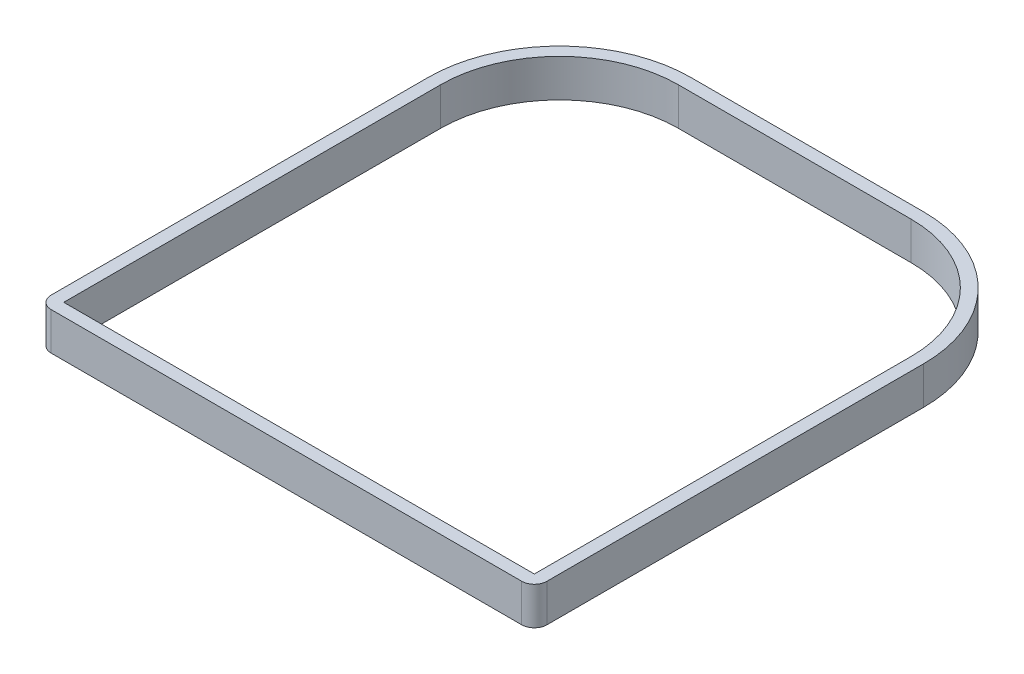
SolidWorks part; units mm, degrees
ref_plane "Front Plane" through (0, 0, 0) normal (0, 0, 1) x (1, 0, 0)
ref_plane "Top Plane" through (0, 0, 0) normal (0, 1, 0) x (1, 0, 0)
ref_plane "Right Plane" through (0, 0, 0) normal (1, 0, 0) x (0, 0, -1)
sketch "Sketch1" plane through (0, 0, 0) normal (0, 1, 0) x (1, 0, 0)
  line L0 (-9.25, 9.25) -> (0, 0) construction
  line L5 (0, 0) -> (9.25, 9.25) construction
  line L8 (-18.7, -20.7) -> (18.7, -20.7)
  line L11 (0, 0) -> (0, -20.7) construction
  line L12 (-9.25, 18.7) -> (9.25, 18.7)
  line L19 (-19.7, 9.25) -> (-19.7, -21.7)
  line L20 (-19.7, -21.7) -> (19.7, -21.7)
  line L21 (19.7, 9.25) -> (19.7, -21.7)
  line L22 (-9.25, 19.7) -> (9.25, 19.7)
  line L23 (18.7, 9.25) -> (18.7, -20.7)
  line L24 (-18.7, 9.25) -> (-18.7, -20.7)
  arc A1 (18.7, 9.25) -> (9.25, 18.7) centre (9.25, 9.25) ccw
  arc A2 (-9.25, 18.7) -> (-18.7, 9.25) centre (-9.25, 9.25) ccw
  arc A5 (19.7, 9.25) -> (9.25, 19.7) centre (9.25, 9.25) ccw
  arc A6 (-9.25, 19.7) -> (-19.7, 9.25) centre (-9.25, 9.25) ccw
  dimension "D1" = 37.4
  dimension "D3" = 9.45
  dimension "D2" = 29.95
  dimension "D4" = 1
extrude "Boss-Extrude1" add sketch "Sketch1" along normal mid plane 3
fillet "Fillet1" radius 1 2 edges at (19.7, 0, 21.7) (-19.7, 0, 21.7)
